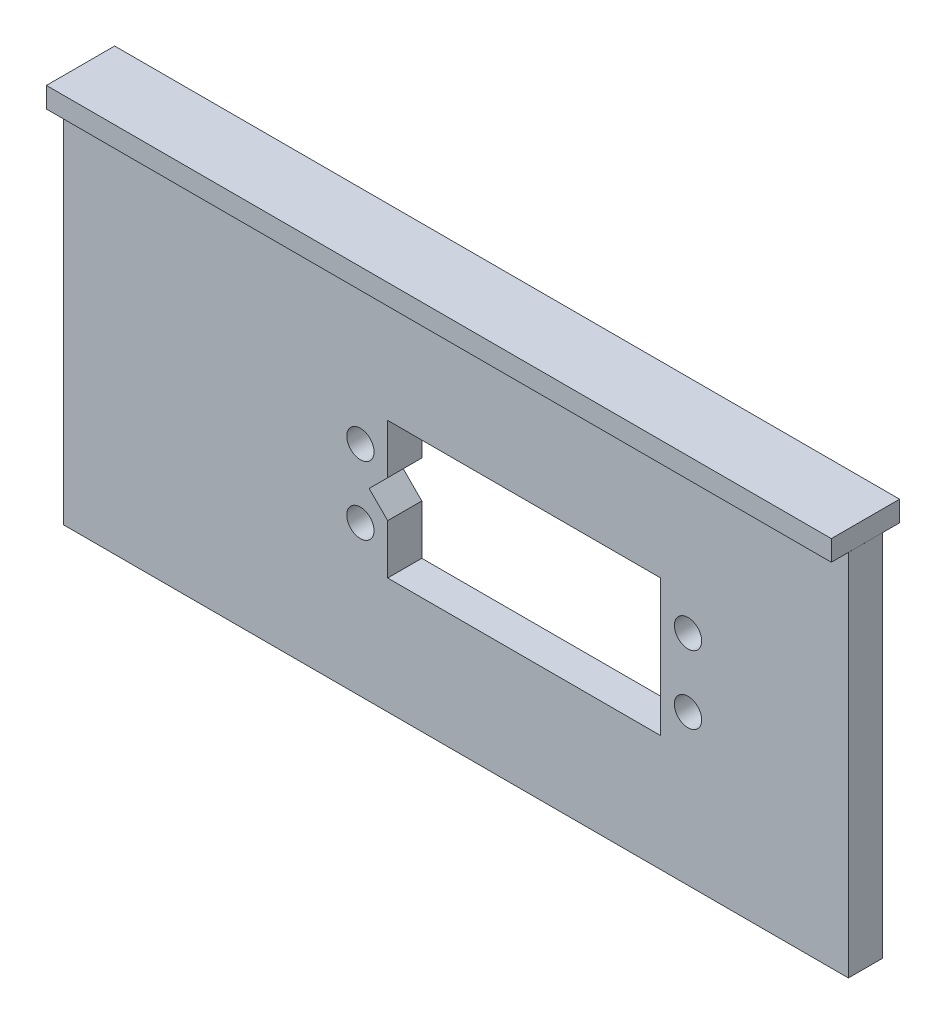
SolidWorks part; units mm, degrees
ref_plane "前基準面" through (0, 0, 0) normal (0, 0, 1) x (1, 0, 0)
ref_plane "上基準面" through (0, 0, 0) normal (0, 1, 0) x (1, 0, 0)
ref_plane "右基準面" through (0, 0, 0) normal (1, 0, 0) x (0, 0, -1)
sketch "草圖1" plane through (0, 0, 0) normal (0, 0, 1) x (1, 0, 0)
  line L1 (-44.4375, 23.5159) -> (70.5625, 23.5159)
  line L2 (-44.4375, 23.5159) -> (-44.4375, -30.4841)
  line L3 (-44.4375, -30.4841) -> (70.5625, -30.4841)
  line L4 (70.5625, 23.5159) -> (70.5625, -30.4841)
  line L5 (13.0625, -30.4841) -> (13.0625, 23.5159) construction
  line L6 (-44.4375, -3.4841) -> (70.5625, -3.4841) construction
  line L7 (3.0625, 6.5159) -> (43.0625, 6.5159)
  line L8 (3.0625, 6.5159) -> (3.0625, -13.4841)
  line L9 (3.0625, -13.4841) -> (43.0625, -13.4841)
  line L10 (43.0625, 6.5159) -> (43.0625, -13.4841)
  line L11 (23.0625, -13.4841) -> (23.0625, 6.5159) construction
  line L12 (3.0625, -3.4841) -> (43.0625, -3.4841) construction
  circle A0 centre (-0.9375, -8.4841) radius 2
  circle A1 centre (47.0625, -8.4841) radius 2
  circle A2 centre (-0.9375, 1.5159) radius 2
  circle A3 centre (47.0625, 1.5159) radius 2
  point P132 (23.0625, -3.4841)
  point P140 (13.0625, -3.4841)
  dimension "D5" = 4
  dimension "D9" = 4
  dimension "D1" = 115
  dimension "D2" = 54
  dimension "D3" = 20
  dimension "D4" = 40
  dimension "D6" = 48
  dimension "D7" = 4
  dimension "D8" = 10
  dimension "D10" = 5
  dimension "D11" = 5
  dimension "D12" = 10
  dimension "D16" = 48
extrude "填料-伸長3" add sketch "草圖1" along normal blind 5 contours A2 | A1 | A0 | L7 L10 L9 L8 | L1 L4 L3 L2 | A3
sketch "草圖3" plane through (0, -30.4841, 0) normal (0, -1, 0) x (1, 0, 0)
  line L0 (-44.4375, 5) -> (70.5625, 5) construction
  line L1 (70.5625, 5) -> (70.5625, 0) construction
  circle A0 centre (29.0625, 2.5) radius 1.75
  circle A1 centre (-2.9375, 2.5) radius 1.75
  dimension "D1" = 3.5
  dimension "D2" = 2.5
  dimension "D3" = 32
  dimension "D4" = 41.5
extrude "除料-伸長2" cut sketch "草圖3" against normal blind 15 contours A1 | A0
sketch "草圖4" plane through (0, 0, 5) normal (0, 0, 1) x (1, 0, 0)
  line L1 (3.0625, 6.5159) -> (3.0625, -13.4841) construction
  line L2 (0.3407, -3.4841) -> (3.0625, -6.2059)
  line L3 (3.0625, -6.2059) -> (3.0625, -0.7623)
  line L4 (3.0625, -0.7623) -> (0.3407, -3.4841)
extrude "除料-伸長3" cut sketch "草圖4" against normal blind 10
sketch "草圖5" plane through (0, 23.5159, 0) normal (0, 1, 0) x (1, 0, 0)
  line L0 (-44.4375, 0) -> (-44.4375, 2.5)
  line L1 (-44.4375, 2.5) -> (70.5603, 2.5)
  line L2 (70.5603, 2.5) -> (70.5603, -7.5)
  line L3 (70.5603, -7.5) -> (-44.4375, -7.5)
  line L4 (-44.4375, -7.5) -> (-44.4375, 0)
  dimension "D1" = 2.5
  dimension "D2" = 7.5
extrude "填料-伸長4" add sketch "草圖5" along normal blind 3
